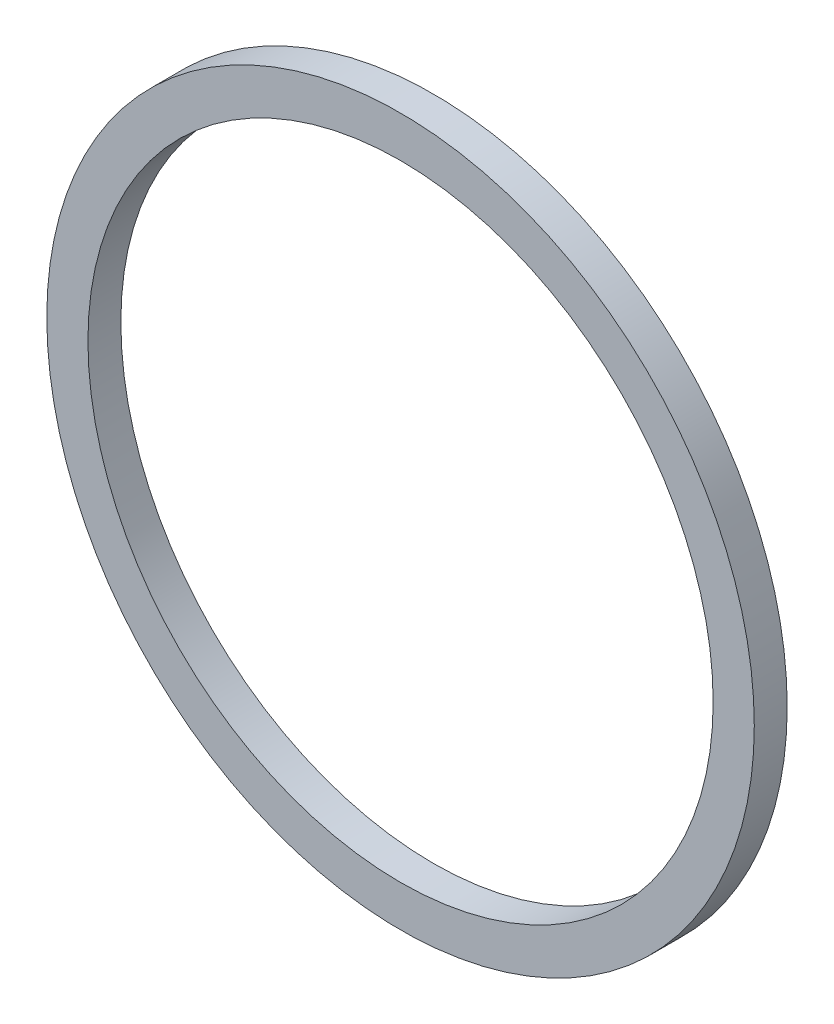
SolidWorks part; units mm, degrees
ref_plane "前视基准面" through (0, 0, 0) normal (0, 0, 1) x (1, 0, 0)
ref_plane "上视基准面" through (0, 0, 0) normal (0, 1, 0) x (1, 0, 0)
ref_plane "右视基准面" through (0, 0, 0) normal (1, 0, 0) x (0, 0, -1)
other "Configuration Table"
sketch "草图1" plane through (0, 0, 0) normal (0, 0, 1) x (1, 0, 0)
  circle A0 centre (0, 0) radius 43
  circle A1 centre (0, 0) radius 38
  dimension "D1" = 86
  dimension "D2" = 5
extrude "凸台-拉伸1" add sketch "草图1" along normal blind 4
